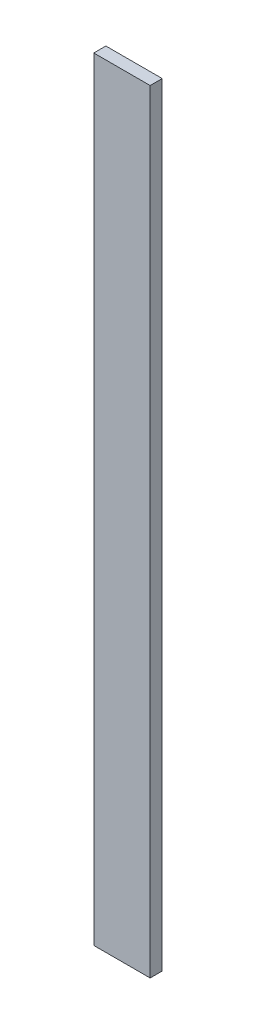
SolidWorks part; units mm, degrees
ref_plane "Front Plane" through (0, 0, 0) normal (0, 0, 1) x (1, 0, 0)
ref_plane "Top Plane" through (0, 0, 0) normal (0, 1, 0) x (1, 0, 0)
ref_plane "Right Plane" through (0, 0, 0) normal (1, 0, 0) x (0, 0, -1)
sketch "Sketch1" plane through (0, 0, 0) normal (0, 1, 0) x (1, 0, 0)
  line L1 (-44.45, -9.525) -> (44.45, -9.525)
  line L2 (-44.45, -9.525) -> (-44.45, 9.525)
  line L3 (-44.45, 9.525) -> (44.45, 9.525)
  line L4 (44.45, -9.525) -> (44.45, 9.525)
  line L5 (-44.45, -9.525) -> (44.45, 9.525) construction
  line L6 (-44.45, 9.525) -> (44.45, -9.525) construction
  point P0 (0, 0)
  dimension "D1" = 19.05
  dimension "D2" = 88.9
extrude "Boss-Extrude1" add sketch "Sketch1" along normal blind 1219.2
